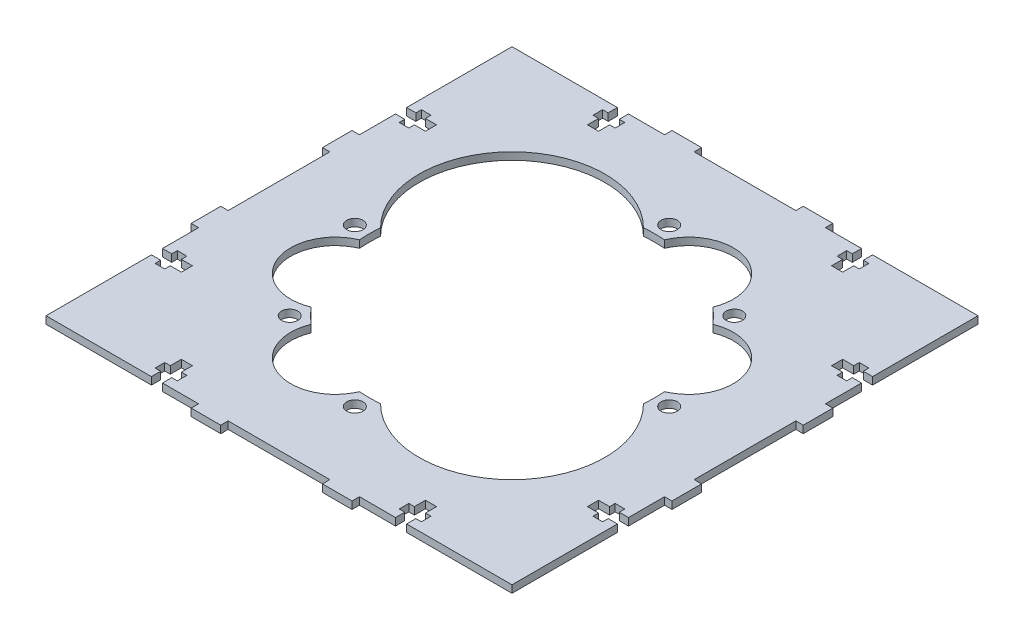
SolidWorks part; units mm, degrees
ref_plane "前视基准面" through (0, 0, 0) normal (0, 0, 1) x (1, 0, 0)
ref_plane "上视基准面" through (0, 0, 0) normal (0, 1, 0) x (1, 0, 0)
ref_plane "右视基准面" through (0, 0, 0) normal (1, 0, 0) x (0, 0, -1)
sketch "草图1" plane through (0, 0, 0) normal (0, 1, 0) x (1, 0, 0)
  line L529 (159.7547, 48.9956) -> (150.0047, 48.9956)
  line L530 (147.0047, 46.4956) -> (145.5047, 46.4956)
  line L531 (150.0047, 46.4956) -> (151.5047, 46.4956)
  line L532 (150.0047, 48.9956) -> (150.0047, 46.4956)
  line L533 (145.5047, 46.4956) -> (145.5047, 43.8956)
  line L534 (145.5047, 43.8956) -> (147.0047, 43.8956)
  line L535 (147.0047, 43.8956) -> (147.0047, 40.8956)
  line L536 (150.0047, 40.8956) -> (147.0047, 40.8956)
  line L537 (150.0047, 43.8956) -> (150.0047, 40.8956)
  line L538 (151.5047, 43.8956) -> (150.0047, 43.8956)
  line L539 (151.5047, 46.4956) -> (151.5047, 43.8956)
  line L540 (147.0047, 46.4956) -> (147.0047, 48.9956)
  line L541 (213.0047, 48.9956) -> (203.2547, 48.9956)
  line L542 (211.5047, 46.4956) -> (211.5047, 43.8956)
  line L543 (216.0047, 46.4956) -> (216.0047, 48.9956)
  line L544 (211.5047, 43.8956) -> (213.0047, 43.8956)
  line L545 (213.0047, 43.8956) -> (213.0047, 40.8956)
  line L546 (213.0047, 40.8956) -> (216.0047, 40.8956)
  line L547 (216.0047, 43.8956) -> (216.0047, 40.8956)
  line L548 (217.5047, 43.8956) -> (216.0047, 43.8956)
  line L549 (217.5047, 46.4956) -> (217.5047, 43.8956)
  line L550 (213.0047, 48.9956) -> (213.0047, 46.4956)
  line L551 (213.0047, 46.4956) -> (211.5047, 46.4956)
  line L552 (216.0047, 46.4956) -> (217.5047, 46.4956)
  line L554 (203.2547, 48.9956) -> (203.2547, 50.9956)
  line L555 (195.2547, 50.9956) -> (195.2547, 48.9956)
  line L556 (195.2547, 48.9956) -> (167.7547, 48.9956)
  line L557 (159.7547, 50.9956) -> (167.7547, 50.9956)
  line L558 (167.7547, 48.9956) -> (167.7547, 50.9956)
  line L559 (159.7547, 50.9956) -> (159.7547, 48.9956)
  line L560 (203.2547, 50.9956) -> (195.2547, 50.9956)
  line L598 (217.0047, 48.9956) -> (216.0047, 48.9956)
  line L602 (244.5047, 7.7456) -> (244.5047, 17.4956)
  line L603 (242.0047, 20.4956) -> (242.0047, 21.9956)
  line L604 (147.0047, 48.9956) -> (138.6047, 48.9956)
  line L605 (242.0047, 17.4956) -> (242.0047, 15.9956)
  line L606 (244.5047, 17.4956) -> (242.0047, 17.4956)
  line L607 (181.5047, -77.0044) -> (181.5047, -65.0044) construction
  line L608 (242.0047, 21.9956) -> (239.4047, 21.9956)
  line L609 (138.6047, 48.9956) -> (133.5047, 48.9956)
  line L613 (217.0047, 48.9956) -> (229.5047, 48.9956)
  line L614 (239.4047, 21.9956) -> (239.4047, 20.4956)
  line L615 (239.4047, 20.4956) -> (236.4047, 20.4956)
  line L616 (236.4047, 17.4956) -> (236.4047, 20.4956)
  line L617 (239.4047, 17.4956) -> (236.4047, 17.4956)
  line L618 (239.4047, 15.9956) -> (239.4047, 17.4956)
  line L619 (242.0047, 15.9956) -> (239.4047, 15.9956)
  line L620 (242.0047, 20.4956) -> (244.5047, 20.4956)
  line L621 (244.5047, -45.5044) -> (244.5047, -35.7544)
  line L622 (242.0047, -44.0044) -> (239.4047, -44.0044)
  line L623 (242.0047, -48.5044) -> (244.5047, -48.5044)
  line L624 (239.4047, -44.0044) -> (239.4047, -45.5044)
  line L625 (239.4047, -45.5044) -> (236.4047, -45.5044)
  line L626 (236.4047, -45.5044) -> (236.4047, -48.5044)
  line L627 (239.4047, -48.5044) -> (236.4047, -48.5044)
  line L628 (239.4047, -50.0044) -> (239.4047, -48.5044)
  line L629 (242.0047, -50.0044) -> (239.4047, -50.0044)
  line L630 (244.5047, -45.5044) -> (242.0047, -45.5044)
  line L631 (242.0047, -45.5044) -> (242.0047, -44.0044)
  line L632 (242.0047, -48.5044) -> (242.0047, -50.0044)
  line L633 (244.5047, -35.7544) -> (246.5047, -35.7544)
  line L634 (246.5047, -27.7544) -> (244.5047, -27.7544)
  line L635 (244.5047, -27.7544) -> (244.5047, -0.2544)
  line L636 (246.5047, 7.7456) -> (246.5047, -0.2544)
  line L637 (244.5047, -0.2544) -> (246.5047, -0.2544)
  line L638 (246.5047, 7.7456) -> (244.5047, 7.7456)
  line L639 (246.5047, -35.7544) -> (246.5047, -27.7544)
  line L640 (244.5047, -49.5044) -> (244.5047, -48.5044)
  line L641 (244.5047, 20.4956) -> (244.5047, 28.8956)
  line L642 (244.5047, 28.8956) -> (244.5047, 33.9956)
  line L643 (244.5047, -49.5044) -> (244.5047, -62.0044)
  line L644 (203.2547, -77.0044) -> (213.0047, -77.0044)
  line L645 (216.0047, -74.5044) -> (217.5047, -74.5044)
  line L646 (213.0047, -74.5044) -> (211.5047, -74.5044)
  line L647 (213.0047, -77.0044) -> (213.0047, -74.5044)
  line L648 (217.5047, -74.5044) -> (217.5047, -71.9044)
  line L649 (217.5047, -71.9044) -> (216.0047, -71.9044)
  line L650 (216.0047, -71.9044) -> (216.0047, -68.9044)
  line L651 (213.0047, -68.9044) -> (216.0047, -68.9044)
  line L652 (213.0047, -71.9044) -> (213.0047, -68.9044)
  line L653 (211.5047, -71.9044) -> (213.0047, -71.9044)
  line L654 (211.5047, -74.5044) -> (211.5047, -71.9044)
  line L655 (216.0047, -74.5044) -> (216.0047, -77.0044)
  line L656 (150.0047, -77.0044) -> (159.7547, -77.0044)
  line L657 (151.5047, -74.5044) -> (151.5047, -71.9044)
  line L658 (147.0047, -74.5044) -> (147.0047, -77.0044)
  line L659 (151.5047, -71.9044) -> (150.0047, -71.9044)
  line L660 (150.0047, -71.9044) -> (150.0047, -68.9044)
  line L661 (150.0047, -68.9044) -> (147.0047, -68.9044)
  line L662 (147.0047, -71.9044) -> (147.0047, -68.9044)
  line L663 (145.5047, -71.9044) -> (147.0047, -71.9044)
  line L664 (145.5047, -74.5044) -> (145.5047, -71.9044)
  line L665 (150.0047, -77.0044) -> (150.0047, -74.5044)
  line L666 (150.0047, -74.5044) -> (151.5047, -74.5044)
  line L667 (147.0047, -74.5044) -> (145.5047, -74.5044)
  line L668 (159.7547, -77.0044) -> (159.7547, -79.0044)
  line L669 (167.7547, -79.0044) -> (167.7547, -77.0044)
  line L670 (167.7547, -77.0044) -> (195.2547, -77.0044)
  line L671 (203.2547, -79.0044) -> (195.2547, -79.0044)
  line L672 (195.2547, -77.0044) -> (195.2547, -79.0044)
  line L673 (203.2547, -79.0044) -> (203.2547, -77.0044)
  line L674 (159.7547, -79.0044) -> (167.7547, -79.0044)
  line L675 (146.0047, -77.0044) -> (147.0047, -77.0044)
  line L676 (216.0047, -77.0044) -> (224.4047, -77.0044)
  line L677 (224.4047, -77.0044) -> (229.5047, -77.0044)
  line L678 (146.0047, -77.0044) -> (133.5047, -77.0044)
  line L679 (118.5047, -35.7544) -> (118.5047, -45.5044)
  line L680 (121.0047, -48.5044) -> (121.0047, -50.0044)
  line L681 (121.0047, -45.5044) -> (121.0047, -44.0044)
  line L682 (118.5047, -45.5044) -> (121.0047, -45.5044)
  line L683 (121.0047, -50.0044) -> (123.6047, -50.0044)
  line L684 (123.6047, -50.0044) -> (123.6047, -48.5044)
  line L685 (123.6047, -48.5044) -> (126.6047, -48.5044)
  line L686 (126.6047, -45.5044) -> (126.6047, -48.5044)
  line L687 (123.6047, -45.5044) -> (126.6047, -45.5044)
  line L688 (123.6047, -44.0044) -> (123.6047, -45.5044)
  line L689 (121.0047, -44.0044) -> (123.6047, -44.0044)
  line L690 (121.0047, -48.5044) -> (118.5047, -48.5044)
  line L691 (118.5047, 17.4956) -> (118.5047, 7.7456)
  line L692 (121.0047, 15.9956) -> (123.6047, 15.9956)
  line L693 (121.0047, 20.4956) -> (118.5047, 20.4956)
  line L694 (123.6047, 15.9956) -> (123.6047, 17.4956)
  line L695 (123.6047, 17.4956) -> (126.6047, 17.4956)
  line L696 (126.6047, 17.4956) -> (126.6047, 20.4956)
  line L697 (123.6047, 20.4956) -> (126.6047, 20.4956)
  line L698 (123.6047, 21.9956) -> (123.6047, 20.4956)
  line L699 (121.0047, 21.9956) -> (123.6047, 21.9956)
  line L700 (118.5047, 17.4956) -> (121.0047, 17.4956)
  line L701 (121.0047, 17.4956) -> (121.0047, 15.9956)
  line L702 (121.0047, 20.4956) -> (121.0047, 21.9956)
  line L703 (118.5047, 7.7456) -> (116.5047, 7.7456)
  line L704 (116.5047, -0.2544) -> (118.5047, -0.2544)
  line L705 (118.5047, -0.2544) -> (118.5047, -27.7544)
  line L706 (116.5047, -35.7544) -> (116.5047, -27.7544)
  line L707 (118.5047, -27.7544) -> (116.5047, -27.7544)
  line L708 (116.5047, -35.7544) -> (118.5047, -35.7544)
  line L709 (116.5047, 7.7456) -> (116.5047, -0.2544)
  line L710 (118.5047, 21.4956) -> (118.5047, 20.4956)
  line L711 (118.5047, -48.5044) -> (118.5047, -56.9044)
  line L712 (118.5047, -56.9044) -> (118.5047, -62.0044)
  line L713 (118.5047, 21.4956) -> (118.5047, 33.9956)
  line L714 (133.5047, 48.9956) -> (118.5047, 48.9956)
  line L715 (118.5047, 48.9956) -> (118.5047, 33.9956)
  line L716 (229.5047, 48.9956) -> (244.5047, 48.9956)
  line L717 (244.5047, 48.9956) -> (244.5047, 33.9956)
  line L718 (244.5047, -62.0044) -> (244.5047, -77.0044)
  line L719 (244.5047, -77.0044) -> (229.5047, -77.0044)
  line L720 (133.5047, -77.0044) -> (118.5047, -77.0044)
  line L721 (118.5047, -77.0044) -> (118.5047, -62.0044)
  circle A5 centre (181.5047, -56.5044) radius 2.2
  circle A6 centre (151.4527, -44.0564) radius 2.2
  circle A7 centre (139.0047, -14.0044) radius 2.2
  circle A11 centre (224.0047, -14.0044) radius 2.2
  circle A15 centre (211.5568, 16.0476) radius 2.2
  circle A18 centre (181.5047, 28.4982) radius 2.2
  circle A40 centre (151.4527, -44.0564) radius 5 construction
  arc A41 (156.3736, -43.1708) -> (152.3384, -39.1355) centre (181.5047, -14.0044) cw
  arc A42 (143.1106, -16.8578) -> (143.1106, -11.151) centre (181.5047, -14.0044) cw
  circle A46 centre (181.5047, -14.0044) radius 38.5 construction
  arc A47 (178.6514, 24.3897) -> (184.3581, 24.3897) centre (181.5047, -14.0044) cw
  arc A49 (206.6358, 15.162) -> (210.6711, 11.1267) centre (181.5047, -14.0044) cw
  arc A52 (219.8989, -11.151) -> (219.8989, -16.8578) centre (181.5047, -14.0044) cw
  arc A53 (152.3384, -39.1355) -> (143.1106, -16.8578) centre (147.7245, -27.9966) cw
  arc A54 (184.3581, -52.3985) -> (178.6514, -52.3985) centre (181.5047, -14.0044) cw
  arc A55 (152.3384, 11.1267) -> (156.3736, 15.162) centre (181.5047, -14.0044) cw [skipped]
  arc A56 (210.6711, -39.1355) -> (206.6358, -43.1708) centre (181.5047, -14.0044) cw [skipped]
  arc A57 (178.6514, -52.3985) -> (156.3736, -43.1708) centre (167.5125, -47.7846) cw
  arc A58 (210.6711, 11.1267) -> (219.8989, -11.151) centre (215.285, -0.0122) cw
  arc A59 (184.3581, 24.3897) -> (206.6358, 15.162) centre (195.497, 19.7759) cw
  arc A60 (219.8989, -16.8578) -> (184.3581, -52.3985) centre (202.1285, -34.6281) cw
  arc A61 (143.1106, -11.151) -> (178.6514, 24.3897) centre (160.881, 6.6193) cw
  point P0 (181.5047, -14.0044)
  point P21 (235.9047, -47.5044)
  point P46 (235.9047, 18.4956)
  point P73 (148.0047, -68.4044)
  point P97 (215.0047, 40.3956)
  point P129 (149.0047, 40.3956)
  point P130 (214.0047, -68.4044)
  point P148 (127.1047, 19.4956)
  point P169 (127.1047, -46.5044)
  dimension "D1" = 8
  dimension "D3" = 4
extrude "凸台-拉伸1" add sketch "草图1" along normal blind 2
sketch "草图8" plane through (0, 0, -48.9956) normal (0, 0, -1) x (-1, 0, 0)
  line L0 (-213.0047, 0) -> (-216.0047, 2)
  circle A0 centre (-214.5047, 1) radius 1.5
sketch "草图9" plane through (244.5047, 0, 0) normal (1, 0, 0) x (0, 0, -1)
  line L0 (20.4956, 1) -> (17.4956, 1) construction
  line L1 (20.4956, 2) -> (20.4956, 0) construction
  line L2 (17.4956, 2) -> (17.4956, 0) construction
  circle A0 centre (18.9956, 1) radius 1.5
